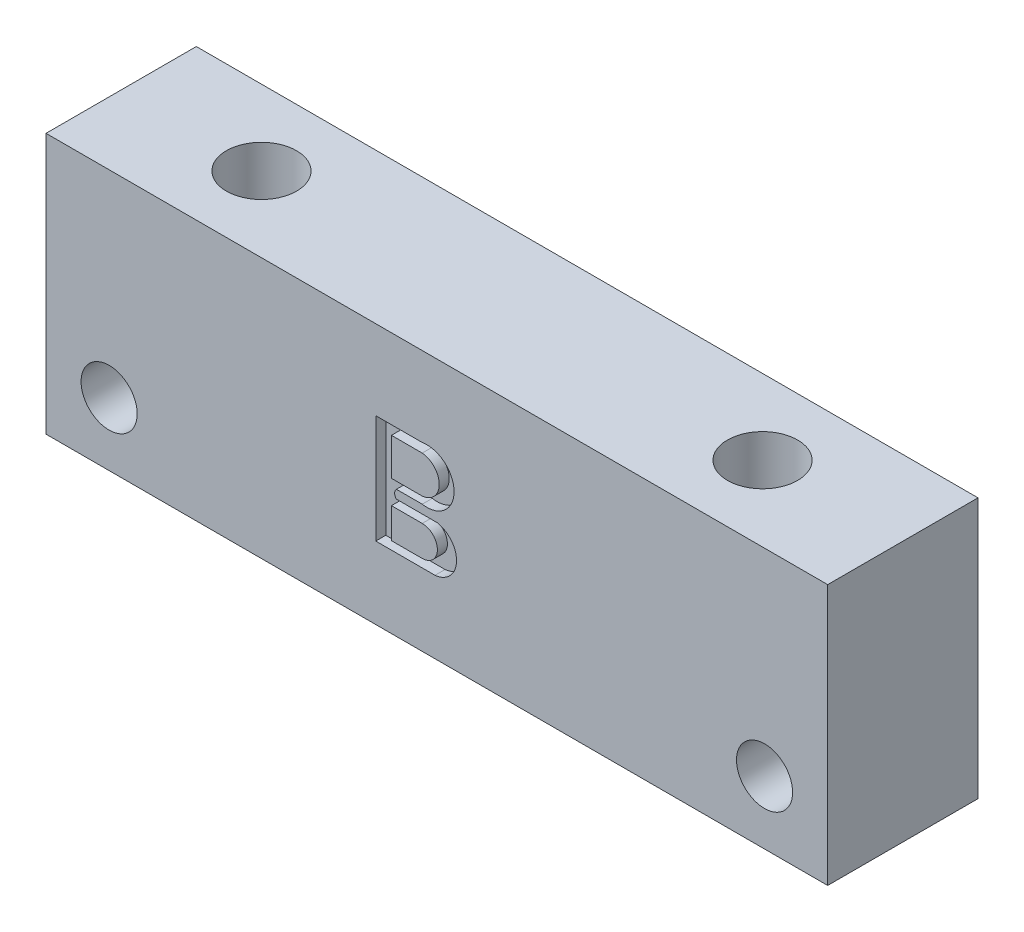
SolidWorks part; units mm, degrees
ref_plane "Front Plane" through (0, 0, 0) normal (0, 0, 1) x (1, 0, 0)
ref_plane "Top Plane" through (0, 0, 0) normal (0, 1, 0) x (1, 0, 0)
ref_plane "Right Plane" through (0, 0, 0) normal (1, 0, 0) x (0, 0, -1)
sketch "Sketch1" plane through (0, 0, 0) normal (0, 0, 1) x (1, 0, 0)
  line L0 (20.7581, -13.3884) -> (20.7581, -0.3884)
  line L2 (20.7581, -0.3884) -> (-18.2419, -0.3884)
  line L3 (-18.2419, -13.3884) -> (20.7581, -13.3884)
  line L4 (-18.2419, -0.3884) -> (-18.2419, -13.3884)
  circle A0 centre (-15.0919, -10.2384) radius 1.4
  circle A1 centre (17.6081, -10.2384) radius 1.4
  dimension "D3" = 2.8
  dimension "D4" = 2.8
  dimension "D5" = 13
extrude "Boss-Extrude2" add sketch "Sketch1" against normal blind 7.5
sketch "Sketch2" plane through (0, -0.3884, 0) normal (0, 1, 0) x (1, 0, 0)
  line L1 (-18.2419, 7.5) -> (-18.2419, 0) construction
  line L2 (20.7581, 7.5) -> (20.7581, 0) construction
  circle A0 centre (-11.2419, 3.75) radius 1.75
  circle A1 centre (13.7581, 3.75) radius 1.75
  dimension "D1" = 3.5
  dimension "D2" = 3.5
  dimension "D3" = 25
  dimension "D4" = 7
  dimension "D5" = 7
extrude "Cut-Extrude1" cut sketch "Sketch2" against normal through all
sketch "Sketch3" plane through (0, 0, 0) normal (0, 0, 1) x (1, 0, 0)
  line L0 (-1.7895, -4.362) -> (0.5284, -4.362)
  line L1 (-1.7895, -4.362) -> (-1.7895, -9.7808)
  line L3 (0.5284, -7.0275) -> (-0.7588, -7.0275)
  line L5 (-0.7588, -7.4536) -> (1.2856, -7.4536)
  line L7 (1.1688, -9.7808) -> (-1.7895, -9.7808)
  line L8 (-1.0065, -4.8193) -> (-1.0065, -6.6782)
  line L9 (-1.0065, -6.6782) -> (0.5284, -6.6782)
  line L11 (0.5284, -4.8193) -> (-1.0065, -4.8193)
  line L12 (-1.0065, -7.8586) -> (-1.0065, -9.373)
  line L13 (-1.0065, -9.373) -> (0.5284, -9.373)
  line L15 (0.5284, -7.8586) -> (-1.0065, -7.8586)
  arc A0 (-0.7588, -7.0275) -> (-0.7588, -7.4536) centre (-0.5458, -7.2406) ccw
  arc A1 (0.5284, -4.8193) -> (0.5284, -6.6782) centre (0.444, -5.7488) cw
  arc A2 (0.5284, -4.362) -> (0.5284, -7.0275) centre (0.7647, -5.6948) cw
  arc A3 (0.5284, -7.8586) -> (0.5284, -9.373) centre (0.5284, -8.6158) cw
  arc A4 (1.2856, -7.4536) -> (1.1688, -9.7808) centre (1.0637, -8.609) cw
extrude "Cut-Extrude2" cut sketch "Sketch3" against normal blind 0.5
